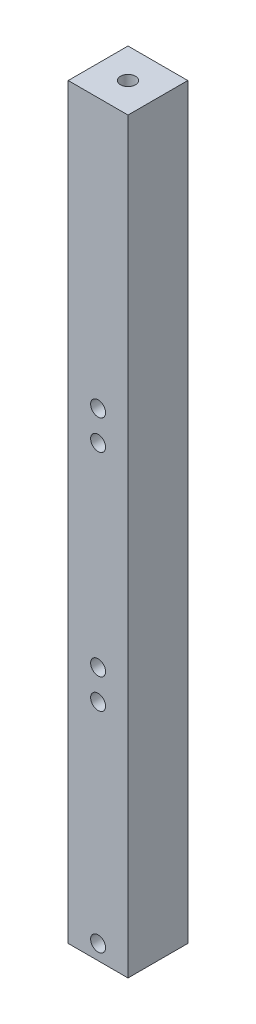
SolidWorks part; units mm, degrees
ref_plane "Front Plane" through (0, 0, 0) normal (0, 0, 1) x (1, 0, 0)
ref_plane "Top Plane" through (0, 0, 0) normal (0, 1, 0) x (1, 0, 0)
ref_plane "Right Plane" through (0, 0, 0) normal (1, 0, 0) x (0, 0, -1)
sketch "Sketch2" plane through (0, 0, 0) normal (0, 1, 0) x (1, 0, 0)
  line L1 (-10, -10) -> (10, -10)
  line L2 (-10, -10) -> (-10, 10)
  line L3 (-10, 10) -> (10, 10)
  line L4 (10, -10) -> (10, 10)
  line L5 (-10, -10) -> (10, 10) construction
  line L6 (-10, 10) -> (10, -10) construction
  circle A0 centre (0, 0) radius 2.5
  point P0 (0, 0)
  dimension "D3" = 5
  dimension "D1" = 20
  dimension "D2" = 20
extrude "Boss-Extrude1" add sketch "Sketch2" along normal blind 250
sketch "Sketch3" plane through (0, 0, 10) normal (0, 0, 1) x (1, 0, 0)
  circle A0 centre (0, 5) radius 2.5
  dimension "D1" = 5
  dimension "D2" = 5
extrude "Cut-Extrude1" cut sketch "Sketch3" against normal through all
sketch "Sketch4" plane through (0, 0, 10) normal (0, 0, 1) x (1, 0, 0)
  line L0 (0, -1000) -> (0, 49000) construction
  line L1 (-10, 0) -> (10, 0) construction
  line L2 (-10, 250) -> (10, 250) construction
  circle A0 centre (0, 75) radius 2.5
  circle A1 centre (0, 85) radius 2.5
  circle A2 centre (0, 150) radius 2.5
  circle A3 centre (0, 160) radius 2.5
  dimension "D1" = 5
  dimension "D2" = 75
  dimension "D4" = 10
  dimension "D5" = 5
  dimension "D6" = 5
  dimension "D7" = 5
  dimension "D8" = 10
  dimension "D3" = 90
extrude "Cut-Extrude2" cut sketch "Sketch4" against normal through all
